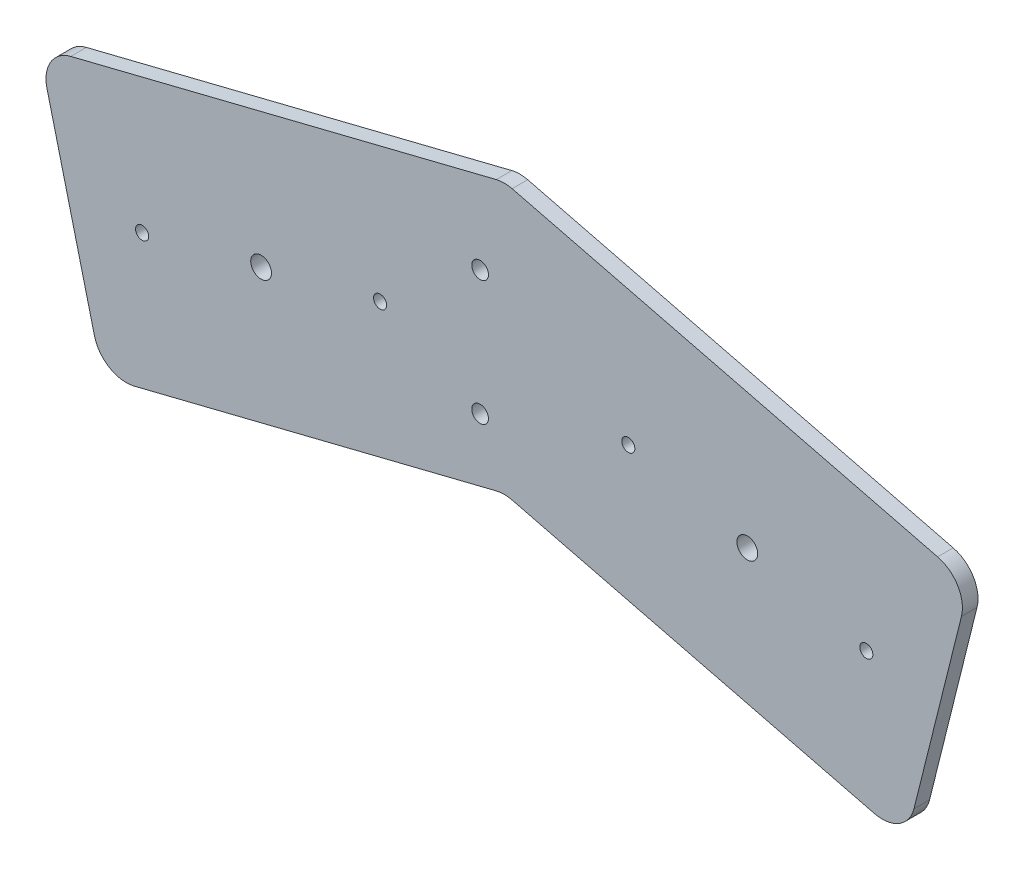
SolidWorks part; units mm, degrees
ref_plane "Front Plane" through (0, 0, 0) normal (0, 0, 1) x (1, 0, 0)
ref_plane "Top Plane" through (0, 0, 0) normal (0, 1, 0) x (1, 0, 0)
ref_plane "Right Plane" through (0, 0, 0) normal (1, 0, 0) x (0, 0, -1)
sketch "Sketch1" plane through (0, 0, 0) normal (0, 0, 1) x (1, 0, 0)
  line L0 (0, 0) -> (-82.5, -20.5696) construction
  line L1 (0, 0) -> (82.5, -20.5696) construction
  line L2 (-82.5, -20.5696) -> (82.5, -20.5696) construction
  line L3 (-82.5, -20.5696) -> (-74.3351, -53.317) construction
  line L4 (82.5, -20.5696) -> (74.3351, -53.317) construction
  line L5 (-74.3351, -53.317) -> (-37.949, -44.245) construction
  line L6 (-74.3351, -53.317) -> (-110.7212, -62.3891) construction
  line L7 (74.3351, -53.317) -> (37.949, -44.245) construction
  line L8 (74.3351, -53.317) -> (110.7212, -62.3891) construction
  line L9 (154.1183, 0) -> (-154.1183, 0) construction
  line L10 (-132.5268, -26.6013) -> (-2.4192, 5.8382)
  line L11 (2.4192, 5.8382) -> (132.5268, -26.6013)
  line L12 (139.8105, -38.7235) -> (125.2952, -96.9412)
  line L13 (113.173, -104.225) -> (2.4192, -76.6109)
  line L14 (-2.4192, -76.6109) -> (-113.173, -104.225)
  line L15 (-125.2952, -96.9412) -> (-139.8105, -38.7235)
  line L16 (0, -20.5696) -> (0, -58.6696) construction
  line L17 (-7.366, -20.5696) -> (-7.366, -58.6696) construction
  arc A0 (-2.4192, 5.8382) -> (2.4192, 5.8382) centre (0, -3.8648) cw
  arc A1 (2.4192, -76.6109) -> (-2.4192, -76.6109) centre (0, -86.3139) ccw
  arc A2 (132.5268, -26.6013) -> (139.8105, -38.7235) centre (130.1076, -36.3043) cw
  arc A3 (125.2952, -96.9412) -> (113.173, -104.225) centre (115.5923, -94.522) cw
  arc A4 (-113.173, -104.225) -> (-125.2952, -96.9412) centre (-115.5923, -94.522) cw
  arc A5 (-132.5268, -26.6013) -> (-139.8105, -38.7235) centre (-130.1076, -36.3043) ccw
  point P21 (0, 6.4413)
  point P24 (0, -76.0078)
  dimension "D13" = 10
  dimension "D1" = 165
  dimension "D2" = 40
  dimension "D3" = 152
  dimension "D4" = 33.75
  dimension "D5" = 33.75
  dimension "D6" = 37.5
  dimension "D7" = 37.5
  dimension "D8" = 37.5
  dimension "D9" = 37.5
  dimension "D10" = 40
  dimension "D11" = 60
  dimension "D12" = 60
  dimension "D14" = 7.366
  dimension "D15" = 38.1
extrude "Boss-Extrude1" add sketch "Sketch1" against normal blind 4.7625
hole_wizard "1/4 (0.25) Diameter Hole2" positions "Sketch9" profile "Sketch10" hole size "1/4" standard "ANSI Inch" end condition through all
sketch "Sketch9" plane through (0, 0, 0) normal (0, 0, 1) x (1, 0, 0)
  point P0 (-74.3351, -53.317)
  point P3 (74.3351, -53.317)
sketch "Sketch10" plane through (-74.3351, -53.317, 0) normal (1, 0, 0) x (0, -1, 0)
  line L0 (0, 0) -> (0, 4.7625)
  line L1 (0, 4.7625) -> (3.175, 4.7625)
  line L2 (3.175, 4.7625) -> (3.175, 0)
  line L5 (3.175, 0) -> (0, 0)
  line L11 (0, -6.35) -> (0, 107.95) construction
  dimension "Thru Hole Dia." = 6.35
  dimension "Thru Hole Depth" = 4.7625
hole_wizard "Ø4.0mm Dowel Hole1" positions "Sketch11" profile "Sketch12" hole size "Ø4.0" standard "ANSI Metric" end condition through all
sketch "Sketch11" plane through (0, 0, 0) normal (0, 0, 1) x (1, 0, 0)
  point P0 (-110.7212, -62.3891)
  point P3 (-37.949, -44.245)
  point P6 (37.949, -44.245)
  point P9 (110.7212, -62.3891)
sketch "Sketch12" plane through (-110.7212, -62.3891, 0) normal (1, 0, 0) x (0, -1, 0)
  line L0 (0, 0) -> (0, 4.7625)
  line L1 (0, 4.7625) -> (2, 4.7625)
  line L2 (2, 4.7625) -> (2, 0)
  line L5 (2, 0) -> (0, 0)
  line L11 (0, -6.35) -> (0, 107.95) construction
  dimension "Thru Hole Dia." = 4
  dimension "Thru Hole Depth" = 4.7625
hole_wizard "1/4-20 Tapped Hole1" positions "Sketch13" profile "Sketch14" tap size "1/4-20" standard "ANSI Inch" end condition through all
sketch "Sketch13" plane through (0, 0, 0) normal (0, 0, 1) x (1, 0, 0)
  point P17 (-7.366, -20.5696)
  point P20 (-7.366, -58.6696)
  point P23 (0, 0)
  point P24 (0, 0)
sketch "Sketch14" plane through (-7.366, -20.5696, 0) normal (1, 0, 0) x (0, -1, 0)
  line L0 (0, 0) -> (0, 4.7625)
  line L1 (0, 4.7625) -> (2.5527, 4.7625)
  line L2 (2.5527, 4.7625) -> (2.5527, 0)
  line L5 (2.5527, 0) -> (0, 0)
  line L11 (0, -6.35) -> (0, 107.95) construction
  dimension "Thru Tap Drill Dia." = 5.1054
  dimension "Thru Tap Drill Depth" = 4.7625
cosmetic thread "Hole Thread1"
cosmetic thread "Hole Thread4"
